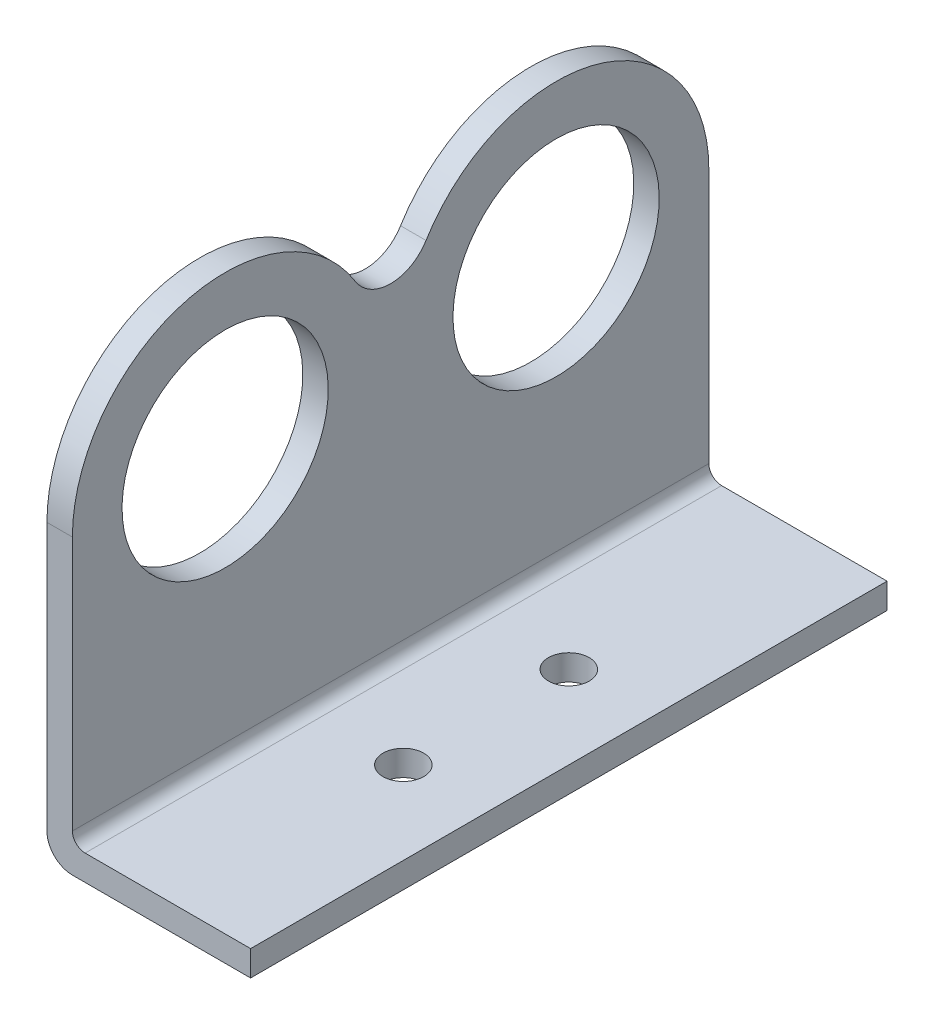
SolidWorks part; units mm, degrees
material "Acrylic (Medium-high impact)"
ref_plane "Front Plane" through (0, 0, 0) normal (0, 0, 1) x (1, 0, 0)
ref_plane "Top Plane" through (0, 0, 0) normal (0, 1, 0) x (1, 0, 0)
ref_plane "Right Plane" through (0, 0, 0) normal (1, 0, 0) x (0, 0, -1)
sketch "Sketch1" plane through (0, 0, 0) normal (0, 0, 1) x (1, 0, 0)
  line L0 (0, 35) -> (0, 2)
  line L1 (2, 0) -> (16, 0)
  line L2 (16, 0) -> (16, 2)
  line L3 (16, 2) -> (3, 2)
  line L4 (2, 3) -> (2, 35)
  line L5 (2, 35) -> (0, 35)
  arc A0 (0, 2) -> (2, 0) centre (2, 2) ccw
  arc A1 (2, 3) -> (3, 2) centre (3, 3) ccw
  point P9 (0, 0)
  dimension "D5" = 2
  dimension "D6" = 1
  dimension "D1" = 2
  dimension "D2" = 2
  dimension "D3" = 35
  dimension "D4" = 16
extrude "Boss-Extrude1" add sketch "Sketch1" along normal blind 50
sketch "Sketch2" plane through (0, 2, 0) normal (0, 1, 0) x (1, 0, 0)
  line L0 (16, -50) -> (3, -50) construction
  line L1 (16, -50) -> (16, 0) construction
  circle A0 centre (9.5, -18.5) radius 1.6
  circle A1 centre (9.5, -31.5) radius 1.6
  dimension "D1" = 3.2
  dimension "D2" = 3.2
  dimension "D3" = 13
  dimension "D4" = 18.5
  dimension "D5" = 6.5
  dimension "D6" = 18.5
extrude "Cut-Extrude1" cut sketch "Sketch2" against normal blind 50
sketch "Sketch3" plane through (2, 0, 0) normal (1, 0, 0) x (0, 0, -1)
  line L0 (-12, 35) -> (0, 35)
  line L1 (-50, 35) -> (0, 35) construction
  line L2 (0, 3) -> (0, 35) construction
  line L3 (-50, 3) -> (-50, 35) construction
  line L4 (-38, 35) -> (-50, 35)
  line L5 (-50, 35) -> (-50, 23)
  line L6 (0, 35) -> (0, 23)
  line L7 (-38, 35) -> (-12, 35)
  line L8 (-50, 0) -> (0, 0) construction
  circle A0 centre (-38, 23) radius 8.1
  circle A1 centre (-12, 23) radius 8.1
  arc A2 (-27.7801, 29.2892) -> (-50, 23) centre (-38, 23) ccw
  arc A3 (0, 23) -> (-22.2199, 29.2892) centre (-12, 23) ccw
  arc A4 (-27.7801, 29.2892) -> (-22.2199, 29.2892) centre (-25, 31) ccw
  line M7 (0, 3) -> (0, 35)
  line M8 (0, 35) -> (-50, 35)
  line M9 (-50, 35) -> (-50, 3)
  dimension "D2" = 16.2
  dimension "D3" = 16.2
  dimension "D1" = 26
  dimension "D4" = 4
  dimension "D5" = 23
  dimension "D6" = 25
extrude "Cut-Extrude2" cut sketch "Sketch3" against normal blind 50 contours A1 | A0 | A2 M8 M9 | A2 A4 A3 M8 | A3 M7 M8
